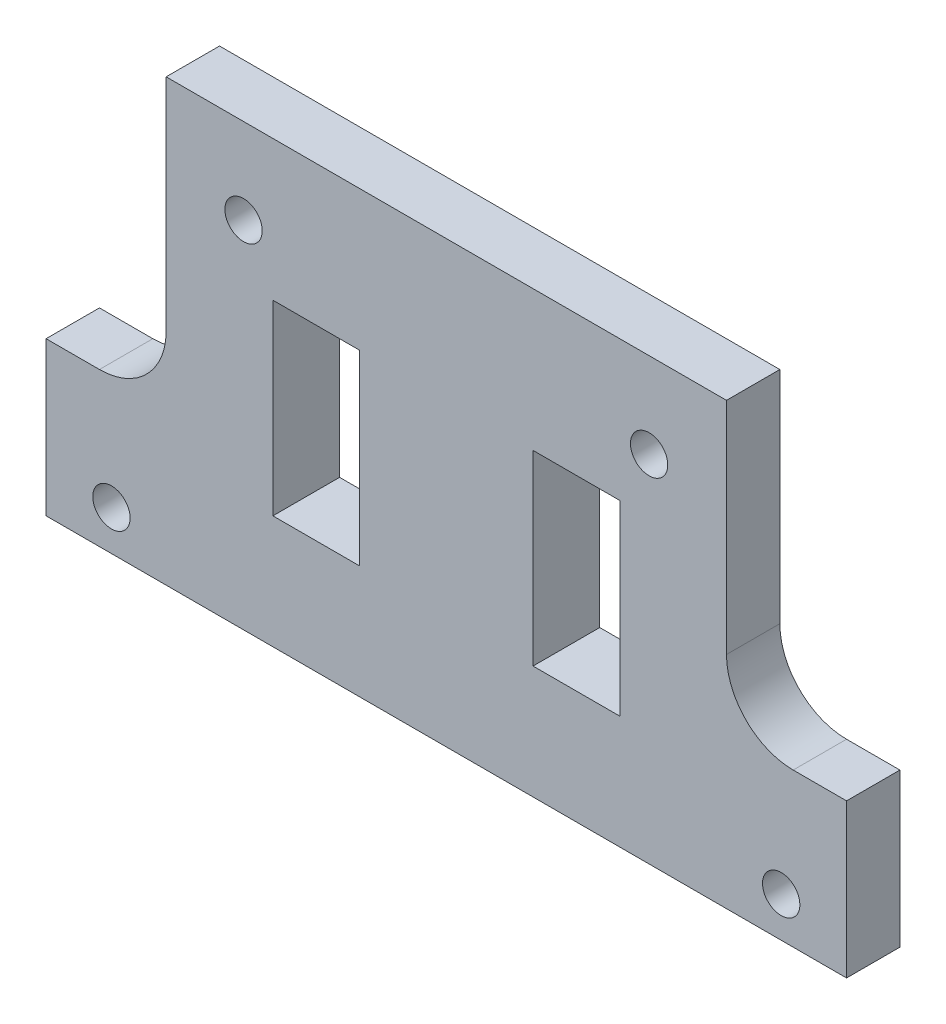
SolidWorks part; units mm, degrees
ref_plane "前视基准面" through (0, 0, 0) normal (0, 0, 1) x (1, 0, 0)
ref_plane "上视基准面" through (0, 0, 0) normal (0, 1, 0) x (1, 0, 0)
ref_plane "右视基准面" through (0, 0, 0) normal (1, 0, 0) x (0, 0, -1)
sketch "草图1" plane through (0, 0, 0) normal (0, 0, 1) x (1, 0, 0)
  line L0 (0, 52.0574) -> (0, -25.7843) construction
  line L1 (30, 0) -> (-30, 0)
  line L2 (-30, 0) -> (-30, 11.5)
  line L3 (-30, 11.5) -> (-21, 11.5)
  line L4 (-21, 11.5) -> (-21, 33)
  line L5 (-21, 33) -> (21, 33)
  line L6 (21, 11.5) -> (21, 33)
  line L7 (30, 11.5) -> (21, 11.5)
  line L8 (30, 0) -> (30, 11.5)
  point P12 (0, 33)
  point P15 (0, 0)
  dimension "D1" = 60
  dimension "D2" = 42
  dimension "D3" = 11.5
  dimension "D4" = 33
extrude "凸台-拉伸1" add sketch "草图1" along normal blind 5
sketch "草图2" plane through (0, 0, 0) normal (0, 0, -1) x (-1, 0, 0)
  line L0 (0, 27.8168) -> (0, -11.5577) construction
  line L1 (30, 0) -> (-30, 0) construction
  line L2 (-13, 22.5) -> (-6.5, 22.5)
  line L3 (-13, 22.5) -> (-13, 8.5)
  line L4 (-13, 8.5) -> (-6.5, 8.5)
  line L5 (-6.5, 22.5) -> (-6.5, 8.5)
  line L6 (-21, 33) -> (21, 33) construction
  line L7 (6.5, 22.5) -> (6.5, 8.5)
  line L8 (13, 8.5) -> (6.5, 8.5)
  line L9 (13, 22.5) -> (13, 8.5)
  line L10 (13, 22.5) -> (6.5, 22.5)
  dimension "D1" = 13
  dimension "D2" = 26
  dimension "D3" = 8.5
  dimension "D4" = 10.5
extrude "切除-拉伸1" cut sketch "草图2" against normal blind 5
sketch "草图3" plane through (0, 0, 0) normal (0, 0, -1) x (-1, 0, 0)
  circle A4 centre (-25.1, 3) radius 1.4
  circle A5 centre (-15.2, 26.6) radius 1.4
  circle A6 centre (25.1, 3) radius 1.4
  circle A7 centre (15.2, 26.6) radius 1.4
extrude "切除-拉伸2" cut sketch "草图3" against normal through all
sketch "草图4" plane through (0, 0, 5) normal (0, 0, -1) x (-1, 0, 0)
  circle A0 centre (-25.1, 3) radius 2.95
  circle A1 centre (-15.2, 26.6) radius 2.95
  circle A2 centre (15.2, 26.6) radius 2.95
  circle A3 centre (25.1, 3) radius 2.95
  dimension "D1" = 5.9
extrude "切除-拉伸4" [suppressed] cut sketch "草图4" along normal blind 2
fillet "圆角1" radius 5 2 edges at (-21, 11.5, 2.5) (21, 11.5, 2.5)
sketch "草图5" plane through (0, 0, 0) normal (0, 0, -1) x (-1, 0, 0)
  line L16 (21, 33) -> (-21, 33)
  line L17 (21, 16.5) -> (21, 33)
  line L18 (30, 11.5) -> (26, 11.5)
  line L19 (30, 0) -> (30, 11.5)
  line L20 (28, 0) -> (30, 0)
  line L21 (28, 10.5) -> (28, 0)
  line L22 (19, 10.5) -> (28, 10.5)
  line L23 (19, 31) -> (19, 10.5)
  line L24 (21, 33) -> (-21, 33)
  line L33 (21, 16.5) -> (21, 33)
  line L34 (30, 11.5) -> (26, 11.5)
  line L35 (30, 0) -> (30, 11.5)
  line L36 (28, 0) -> (30, 0)
  line L37 (28, 10.5) -> (28, 0)
  line L38 (19, 10.5) -> (28, 10.5)
  line L39 (19, 31) -> (19, 10.5)
  line L96 (-19, 31) -> (19, 31)
  line L97 (-19, 31) -> (19, 31)
  line L98 (-19, 10.5) -> (-19, 31)
  line L99 (-19, 10.5) -> (-19, 31)
  line L100 (-28, 10.5) -> (-19, 10.5)
  line L101 (-28, 10.5) -> (-19, 10.5)
  line L102 (-28, 0) -> (-28, 10.5)
  line L103 (-28, 0) -> (-28, 10.5)
  line L104 (-30, 0) -> (-28, 0)
  line L105 (-30, 0) -> (-28, 0)
  line L106 (-30, 11.5) -> (-30, 0)
  line L107 (-30, 11.5) -> (-30, 0)
  line L108 (-26, 11.5) -> (-30, 11.5)
  line L109 (-26, 11.5) -> (-30, 11.5)
  line L110 (-21, 33) -> (-21, 16.5)
  line L111 (-21, 33) -> (-21, 16.5)
  arc A2 (21, 16.5) -> (26, 11.5) centre (26, 16.5) ccw
  arc A4 (21, 16.5) -> (26, 11.5) centre (26, 16.5) ccw
  arc A12 (-26, 11.5) -> (-21, 16.5) centre (-26, 16.5) ccw
  arc A13 (-26, 11.5) -> (-21, 16.5) centre (-26, 16.5) ccw
  dimension "D1" = 0
extrude "切除-拉伸5" cut sketch "草图5" against normal blind 1
